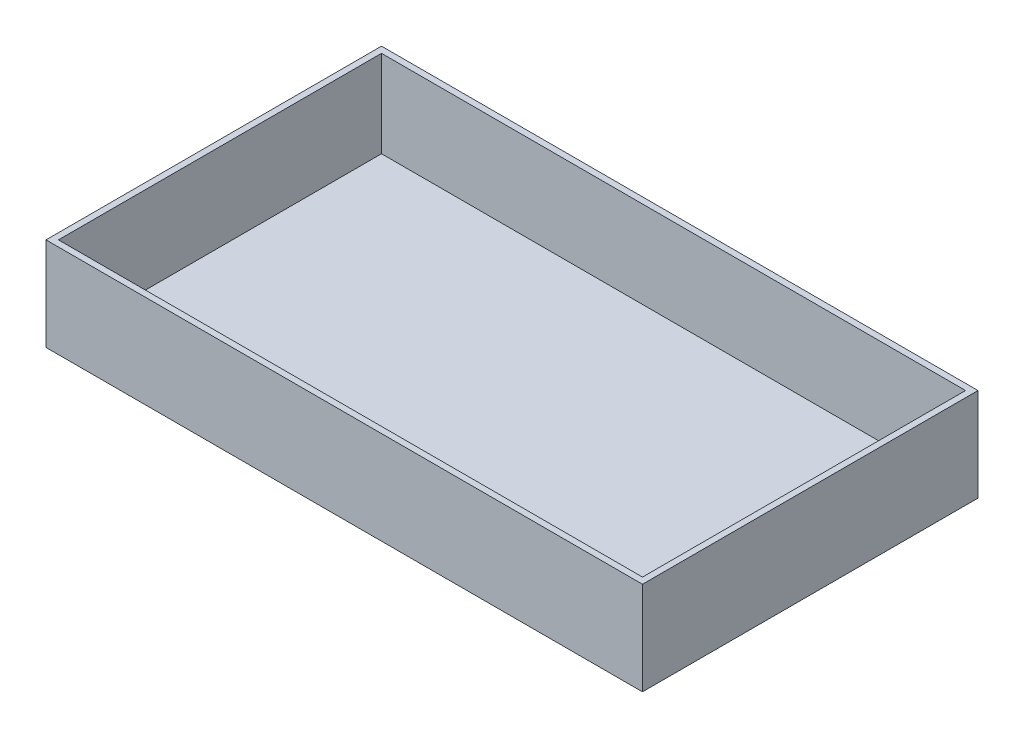
SolidWorks part; units mm, degrees
ref_plane "正面" through (0, 0, 0) normal (0, 0, 1) x (1, 0, 0)
ref_plane "平面" through (0, 0, 0) normal (0, 1, 0) x (1, 0, 0)
ref_plane "右側面" through (0, 0, 0) normal (1, 0, 0) x (0, 0, -1)
sketch "ｽｹｯﾁ1" plane through (0, 0, 0) normal (0, 1, 0) x (1, 0, 0)
  line L1 (-240, 135) -> (240, 135)
  line L2 (-240, 135) -> (-240, -135)
  line L3 (-240, -135) -> (240, -135)
  line L4 (240, 135) -> (240, -135)
  line L5 (-240, 135) -> (240, -135) construction
  line L6 (-240, -135) -> (240, 135) construction
  point P0 (0, 0)
  dimension "D1" = 270
  dimension "600" = 480
extrude "ﾎﾞｽ - 押し出し1" add sketch "ｽｹｯﾁ1" along normal blind 75
shell "ｼｪﾙ1" thickness 5
